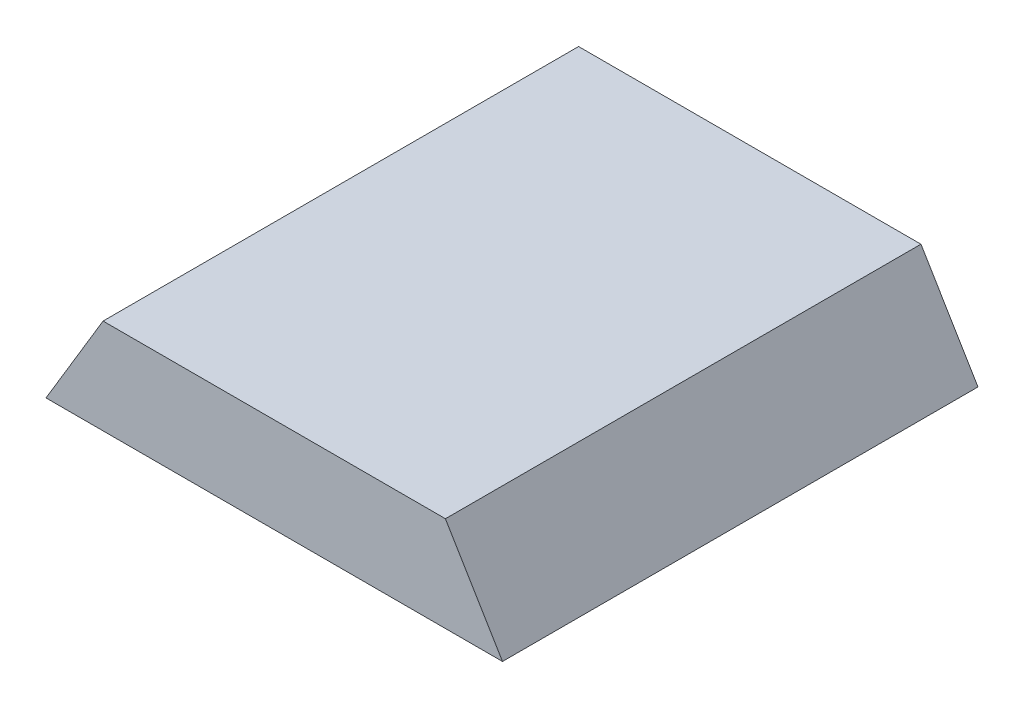
SolidWorks part; units mm, degrees
material "ABS"
ref_plane "Front Plane" through (0, 0, 0) normal (0, 0, 1) x (1, 0, 0)
ref_plane "Top Plane" through (0, 0, 0) normal (0, 1, 0) x (1, 0, 0)
ref_plane "Right Plane" through (0, 0, 0) normal (1, 0, 0) x (0, 0, -1)
sketch "Sketch1" plane through (0, 0, 0) normal (0, 0, 1) x (1, 0, 0)
  line L0 (-120, 0) -> (120, 0)
  line L1 (120, 0) -> (90, 50)
  line L2 (90, 50) -> (-90, 50)
  line L3 (-90, 50) -> (-120, 0)
  point P4 (0, 50)
  point P6 (0, 0)
  point P7 (-1946.7266, 1110.3336)
  dimension "D1" = 240
  dimension "D2" = 180
  dimension "D3" = 50
extrude "Boss-Extrude1" add sketch "Sketch1" against normal blind 250 contours L2 L3 L0 L1
sketch "Sketch2" plane through (0, 0, 0) normal (0, -1, 0) x (1, 0, 0)
  line L4 (120, 0) -> (-120, 0)
  line L5 (-120, 0) -> (-120, -250)
  line L6 (-120, -250) -> (120, -250)
  line L7 (120, -250) -> (120, 0)
  line L8 (120, 0) -> (-120, 0)
  line L9 (-120, 0) -> (-120, -250)
  line L10 (-120, -250) -> (120, -250)
  line L11 (120, -250) -> (120, 0)
  circle A0 centre (0, -120) radius 7.5
  point P6 (0, 0)
  dimension "D2" = 15
  dimension "D3" = 120
  dimension "D1" = 0
extrude "Cut-Extrude1" cut sketch "Sketch2" against normal blind 10 contours A0
